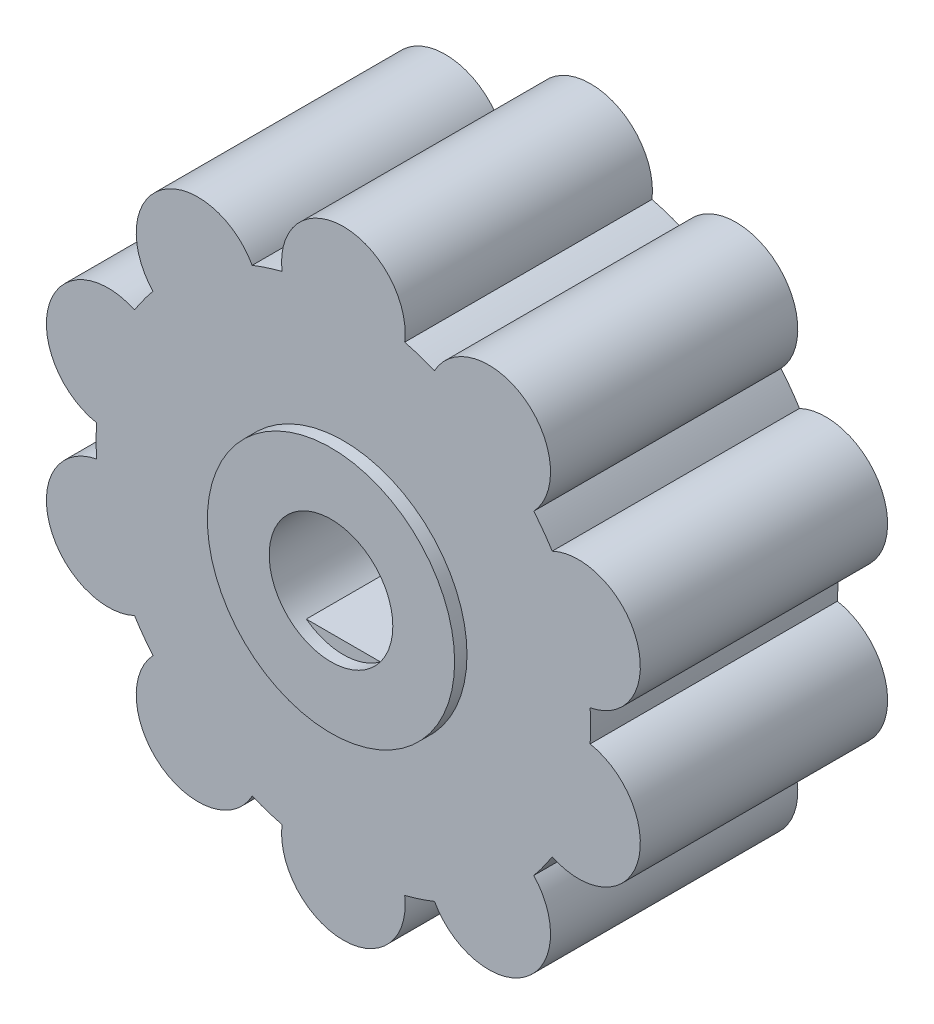
SolidWorks part; units mm, degrees
ref_plane "Ebene vorne" through (0, 0, 0) normal (0, 0, 1) x (1, 0, 0)
ref_plane "Ebene oben" through (0, 0, 0) normal (0, 1, 0) x (1, 0, 0)
ref_plane "Ebene rechts" through (0, 0, 0) normal (1, 0, 0) x (0, 0, -1)
sketch "Skizze1" plane through (0, 0, 0) normal (0, 0, 1) x (1, 0, 0)
  circle A0 centre (0, 0) radius 10
extrude "Aufsatz-Linear austragen1" add sketch "Skizze1" along normal blind 10
ref_plane "Ebene1" through (0, 0, 0) normal (0, 0, -1) x (-1, 0, 0)
sketch "Skizze5" plane through (0, 0, 10) normal (0, 0, 1) x (1, 0, 0)
  circle A0 centre (0, 0) radius 5
  dimension "D1" = 10
extrude "Aufsatz-Linear austragen4" add sketch "Skizze5" along normal blind 0.5 and the other way blind 10.5
sketch "Skizze2" plane through (0, 0, 0) normal (0, 0, -1) x (-1, 0, 0)
  circle A0 centre (0, 10) radius 2.5
  circle A1 centre (0, 0) radius 10 construction
extrude "Aufsatz-Linear austragen2" add sketch "Skizze2" against normal blind 10
pattern_circular "Kreismuster1" count 10 over 360 about axis through (0, 0, 0) along (0, 0, 1) of "Aufsatz-Linear austragen2"
sketch "Skizze3" plane through (0, 0, 10) normal (0, 0, 1) x (1, 0, 0)
  circle A0 centre (0, 0) radius 2.5
  dimension "D1" = 5
extrude "Schnitt-Linear austragen1" cut sketch "Skizze3" against normal blind 20 and the other way blind 0.5 contours A0
ref_plane "Ebene2" through (0, 0, 10) normal (0, 0, 1) x (1, 0, 0)
sketch "Skizze4" plane through (0, 0, 10) normal (0, 0, 1) x (1, 0, 0)
  line L1 (-1.5, -2) -> (1.6217, -2)
  line L2 (-1.5, -2) -> (-1.5, -3.1357)
  line L3 (-1.5, -3.1357) -> (1.6217, -3.1357)
  line L4 (1.6217, -2) -> (1.6217, -3.1357)
  circle A0 centre (0, 0) radius 2.5 construction
  point P6 (0.0608, -2)
  dimension "D1" = 2
extrude "Aufsatz-Linear austragen3" add sketch "Skizze4" against normal blind 10
